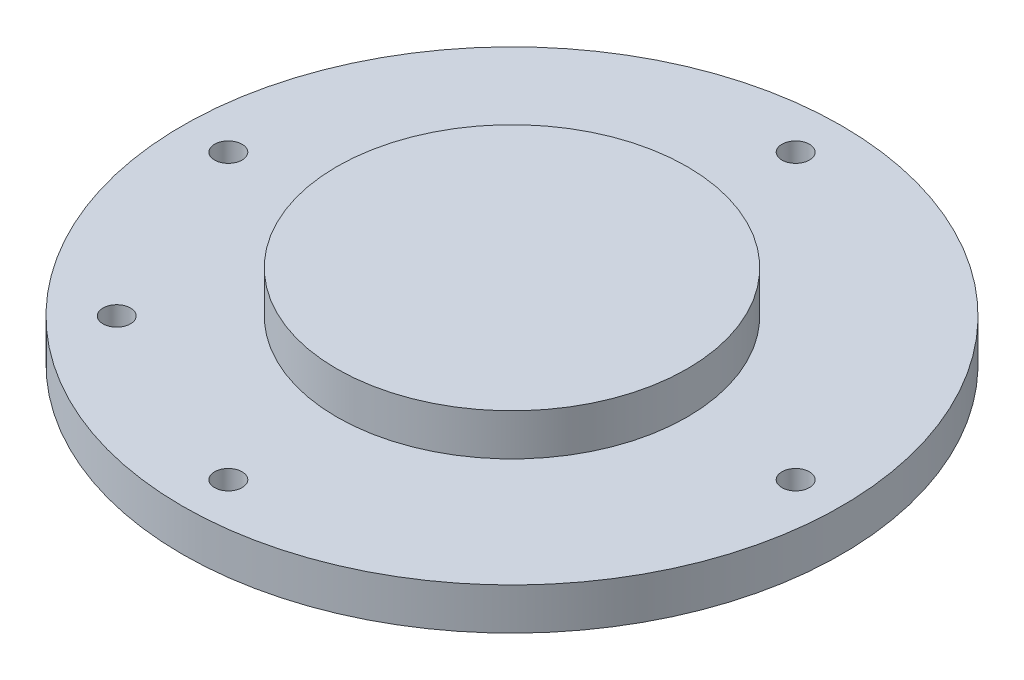
SolidWorks part; units mm, degrees
ref_plane "Front" through (0, 0, 0) normal (0, 0, 1) x (1, 0, 0)
ref_plane "Top" through (0, 0, 0) normal (0, 1, 0) x (1, 0, 0)
ref_plane "Side" through (0, 0, 0) normal (1, 0, 0) x (0, 0, -1)
sketch "Sketch2" plane through (0, 0, 0) normal (0, 0, 1) x (1, 0, 0)
  line L0 (0, 0) -> (0, 48.8324) construction
  line L1 (0, 0) -> (-39.5, 0)
  line L2 (-39.5, 0) -> (-39.5, 5)
  line L3 (-39.5, 5) -> (-21, 5)
  line L4 (-21, 5) -> (-21, 10)
  line L5 (-21, 10) -> (0, 10)
  line L6 (0, 10) -> (0, 0)
  line L7 (-16, 0) -> (-16, 5)
  line L8 (-16, 5) -> (0, 5)
  point P10 (-21, 7.5)
  dimension "D1" = 39.5
  dimension "D2" = 42
  dimension "D3" = 32
  dimension "D4" = 5
  dimension "D5" = 5
  dimension "D6" = 5
revolve "Revolve1" add sketch "Sketch2" angle 360 about L0
sketch "Sketch3" plane through (0, 0, 0) normal (0, -1, 0) x (1, 0, 0)
  circle A0 centre (0, 0) radius 19.5
  circle A1 centre (0, 0) radius 22.5
  dimension "D3" = 45
  dimension "D4" = 45
  dimension "D5" = 39
extrude "Cut-Extrude3" cut sketch "Sketch3" against normal blind 1.68 contours A1 | A0
sketch "Sketch4" plane through (0, 0, 0) normal (0, -1, 0) x (-1, 0, 0)
  circle A0 centre (0, 0) radius 25.5
  circle A1 centre (0, 0) radius 28
  dimension "D1" = 56
  dimension "D2" = 51
extrude "Cut-Extrude4" cut sketch "Sketch4" against normal blind 2.45 contours A1 | A0
sketch "Sketch6" plane through (0, 0, 0) normal (0, -1, 0) x (-1, 0, 0)
  circle A0 centre (0, 0) radius 34
  dimension "D1" = 68
hole_wizard "M4x0.7 Tapped Hole1" positions "Sketch7" profile "Sketch8" tap size "M4x0.7" standard "ANSI Metric" end condition through all
sketch "Sketch7" plane through (0, 0, 0) normal (0, -1, 0) x (-1, 0, 0)
  circle A0 centre (0, 0) radius 34 construction
  point P0 (0, -34)
sketch "Sketch8" plane through (0, 0, 34) normal (1, 0, 0) x (0, 0, -1)
  line L0 (0, 0) -> (0, 10)
  line L1 (0, 10) -> (1.65, 10)
  line L2 (1.65, 10) -> (1.65, 0)
  line L5 (1.65, 0) -> (0, 0)
  line L11 (0, -6.35) -> (0, 107.95) construction
  dimension "Thru Tap Drill Dia." = 3.3
  dimension "Thru Tap Drill Depth" = 10
cosmetic thread "Hole Thread1" parameters "D2"=4
pattern_circular "CirPattern1" count 4 over 360 about axis through (0, 0, 0) along (0, 1, 0) of "M4x0.7 Tapped Hole1"
hole_wizard "M4x0.7 Tapped Hole2" positions "Sketch9" profile "Sketch10" tap size "M4x0.7" standard "ANSI Metric" end condition through all
sketch "Sketch9" plane through (0, 0, 0) normal (0, -1, 0) x (-1, 0, 0)
  point P0 (23.6881, -23.6881)
sketch "Sketch10" plane through (-23.6881, 0, 23.6881) normal (1, 0, 0) x (0, 0, -1)
  line L0 (0, 0) -> (0, 10)
  line L1 (0, 10) -> (1.65, 10)
  line L2 (1.65, 10) -> (1.65, 0)
  line L5 (1.65, 0) -> (0, 0)
  line L11 (0, -6.35) -> (0, 107.95) construction
  dimension "Thru Tap Drill Dia." = 3.3
  dimension "Thru Tap Drill Depth" = 10
cosmetic thread "Hole Thread2" parameters "D2"=4
